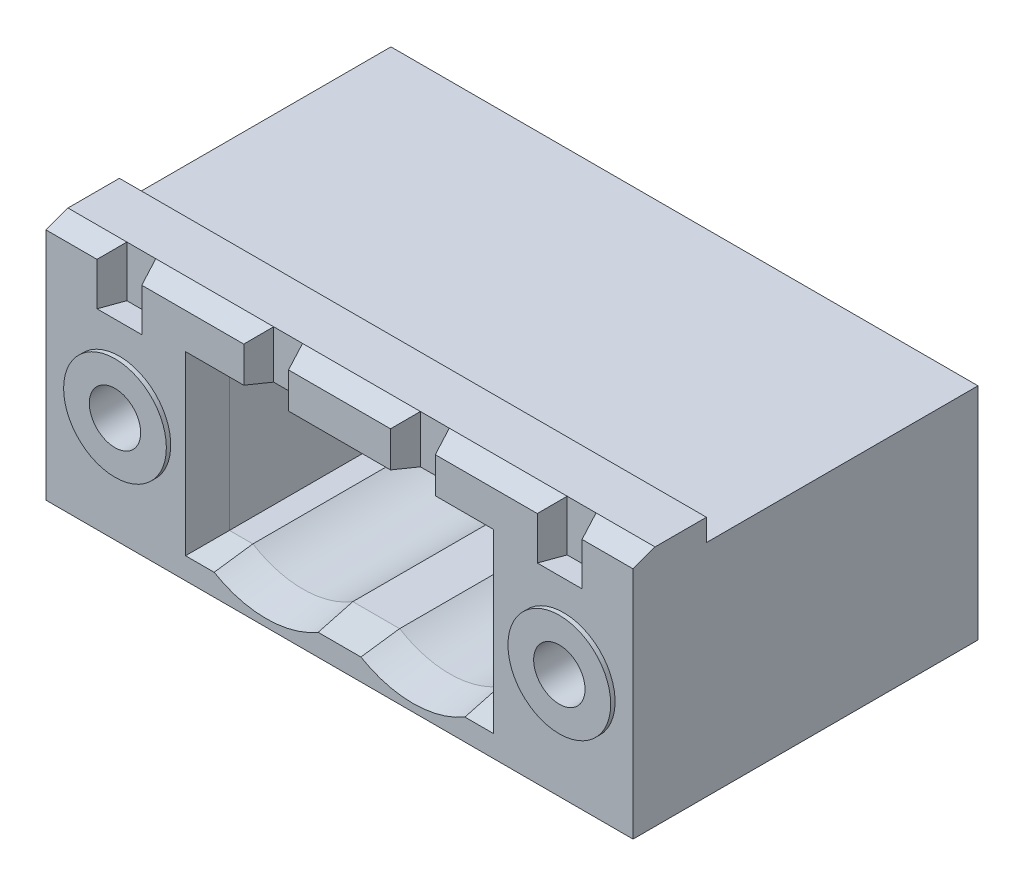
SolidWorks part; units mm, degrees
ref_plane "Front Plane" through (0, 0, 0) normal (0, 0, 1) x (1, 0, 0)
ref_plane "Top Plane" through (0, 0, 0) normal (0, 1, 0) x (1, 0, 0)
ref_plane "Right Plane" through (0, 0, 0) normal (1, 0, 0) x (0, 0, -1)
sketch "Sketch1" plane through (0, 0, 0) normal (1, 0, 0) x (0, 0, -1)
  line L0 (-9.94, -3.81) -> (2, -3.81)
  line L1 (2, -3.81) -> (2, 3.81)
  line L2 (2, 3.81) -> (-7.4, 3.81)
  line L3 (-7.4, 3.81) -> (-7.4, 4.57)
  line L4 (-7.4, 4.57) -> (-9.18, 4.57)
  line L5 (-9.18, 4.57) -> (-9.94, 4.293)
  line L6 (-9.94, 4.293) -> (-9.94, -3.81)
  line L7 (-156.8438, 0) -> (7685.346, 0) construction
  line L8 (0, 0) -> (0, 7842.1898) construction
  point P12 (2, 0)
  dimension "D1" = 11.94
  dimension "D2" = 7.62
  dimension "D3" = 2.54
  dimension "D4" = 0.76
  dimension "D5" = 0.277
  dimension "D6" = 0.76
  dimension "D7" = 2
extrude "Boss-Extrude1" add sketch "Sketch1" along normal mid plane 20.32
sketch "Sketch2" plane through (0, 0, 9.94) normal (0, 0, 1) x (1, 0, 0)
  line L0 (-0.8097, -2.81) -> (0.8097, -2.81)
  line L1 (-5.08, 2.81) -> (5.08, 2.81)
  line L2 (-5.08, 2.81) -> (-5.08, -2.81)
  line L3 (-5.08, -2.81) -> (-4.2703, -2.81)
  line L4 (5.08, 2.81) -> (5.08, -2.81)
  line L5 (4.2703, -2.81) -> (5.08, -2.81)
  arc A0 (-4.2703, -2.81) -> (-0.8097, -2.81) centre (-2.54, 0) ccw
  arc A1 (0.8097, -2.81) -> (4.2703, -2.81) centre (2.54, 0) ccw
  point P4 (0, 2.81)
  point P6 (5.08, 0)
  dimension "D3" = 3.3
  dimension "D1" = 10.16
  dimension "D2" = 5.62
  dimension "D4" = 2.54
  dimension "D5" = 2.54
extrude "Cut-Extrude1" cut sketch "Sketch2" against normal blind 10
chamfer "Chamfer1" distance 0.25 distance2 1.27 8 edges at (-5.08, 0, 9.94) (-4.6751, -2.81, 9.94) (-2.54, -3.3, 9.94) (0, -2.81, 9.94) (2.54, -3.3, 9.94) (4.6751, -2.81, 9.94) (5.08, 0, 9.94) (0, 2.81, 9.94)
sketch "Sketch3" plane through (0, 0, 9.94) normal (0, 0, 1) x (1, 0, 0)
  line L0 (0, 0) -> (-50000, 0) construction
  line L1 (-10.16, 4.293) -> (-10.16, -3.81) construction
  line L2 (0, 0) -> (0, 50000) construction
  line L3 (10.16, 4.293) -> (10.16, -3.81) construction
  circle A0 centre (-7.62, 0) radius 1.778
  circle A1 centre (7.76, 0) radius 1.778
  dimension "D1" = 2.54
  dimension "D2" = 3.556
  dimension "D3" = 2.4
extrude "Boss-Extrude2" add sketch "Sketch3" along normal blind 0.152
sketch "Sketch4" plane through (0, 0, 10.092) normal (0, 0, 1) x (1, 0, 0)
  circle A0 centre (-7.62, 0) radius 0.889
  circle A1 centre (7.76, 0) radius 0.889
  dimension "D1" = 1.778
extrude "Cut-Extrude2" cut sketch "Sketch4" against normal blind 5.08
sketch "Sketch5" plane through (0, 0, -0.06) normal (0, 0, 1) x (1, 0, 0)
  line L0 (0, 0) -> (-50000, 0) construction
  line L1 (0, 0) -> (0, 50000) construction
  line L2 (-2.54, -1000) -> (-2.54, 49000) construction
  line L3 (-3.175, 2.81) -> (-3.175, 1.6629)
  line L4 (5.08, 2.81) -> (-5.08, 2.81) construction
  line L5 (-1.905, 2.81) -> (-1.905, 1.6629)
  line L6 (-3.175, -1.6629) -> (-3.175, -3.2383)
  line L7 (-1.905, -1.6629) -> (-1.905, -3.2383)
  line L8 (-3.175, 2.81) -> (-1.905, 2.81)
  line L9 (-4.2029, 0.635) -> (-5.08, 0.635)
  line L10 (-5.08, 2.81) -> (-5.08, -2.81) construction
  line L11 (-5.08, 0.635) -> (-5.08, -0.635)
  line L12 (-5.08, -0.635) -> (-4.2029, -0.635)
  line L13 (-0.8771, 0.635) -> (0, 0.635)
  line L14 (0, 0.635) -> (0, -0.635)
  line L15 (0, -0.635) -> (-0.8771, -0.635)
  arc A0 (-3.175, 1.6629) -> (-4.2029, 0.635) centre (-2.54, 0) ccw
  arc A1 (-4.2703, -2.81) -> (-0.8097, -2.81) centre (-2.54, 0) ccw construction
  arc A2 (-4.2703, -2.81) -> (-0.8097, -2.81) centre (-2.54, 0) ccw construction
  arc A3 (-1.905, -1.6629) -> (-0.8771, -0.635) centre (-2.54, 0) ccw
  arc A4 (-3.175, -3.2383) -> (-1.905, -3.2383) centre (-2.54, 0) ccw
  arc A5 (-4.2029, -0.635) -> (-3.175, -1.6629) centre (-2.54, 0) ccw
  arc A6 (-0.8771, 0.635) -> (-1.905, 1.6629) centre (-2.54, 0) ccw
  dimension "D2" = 1.78
  dimension "D1" = 2.54
  dimension "D3" = 1.27
  dimension "D4" = 1.27
extrude "Boss-Extrude3" add sketch "Sketch5" along normal blind 0.9525
mirror "Mirror1" about plane through (0, 0, 0) normal (1, 0, 0) of "Boss-Extrude3"
sketch "Sketch8" plane through (0, 0, 0.8925) normal (0, 0, 1) x (1, 0, 0)
  line L0 (0, 0) -> (-50000, 0) construction
  line L1 (-4.2029, 0.635) -> (-3.4904, 0.635)
  line L2 (0.8771, 0.635) -> (1.5896, 0.635)
  line L3 (-1.5896, 0.635) -> (-0.8771, 0.635)
  line L4 (3.4904, 0.635) -> (4.2029, 0.635)
  line L19 (-1.905, 2.81) -> (-3.175, 2.81)
  line L20 (-3.175, 2.81) -> (-3.175, 1.6629)
  line L21 (-4.2029, 0.635) -> (-5.08, 0.635)
  line L22 (-5.08, 0.635) -> (-5.08, -0.635)
  line L23 (-5.08, -0.635) -> (-4.2029, -0.635)
  line L24 (-3.175, -1.6629) -> (-3.175, -3.2383)
  line L25 (-1.905, -3.2383) -> (-1.905, -1.6629)
  line L26 (-0.8771, -0.635) -> (0.8771, -0.635)
  line L27 (1.905, -1.6629) -> (1.905, -3.2383)
  line L28 (3.175, -3.2383) -> (3.175, -1.6629)
  line L29 (4.2029, -0.635) -> (5.08, -0.635)
  line L30 (5.08, -0.635) -> (5.08, 0.635)
  line L31 (5.08, 0.635) -> (4.2029, 0.635)
  line L32 (3.175, 1.6629) -> (3.175, 2.81)
  line L33 (3.175, 2.81) -> (1.905, 2.81)
  line L34 (1.905, 2.81) -> (1.905, 1.6629)
  line L35 (0.8771, 0.635) -> (-0.8771, 0.635)
  line L36 (-1.905, 1.6629) -> (-1.905, 2.81)
  line L39 (-4.2029, 0.635) -> (-5.08, 0.635)
  line L40 (-5.08, 0.635) -> (-5.08, -0.635)
  line L41 (-5.08, -0.635) -> (-4.2029, -0.635)
  line L42 (-3.175, -1.6629) -> (-3.175, -3.2383)
  line L43 (-1.905, -3.2383) -> (-1.905, -1.6629)
  line L44 (-0.8771, -0.635) -> (0.8771, -0.635)
  line L45 (1.905, -1.6629) -> (1.905, -3.2383)
  line L46 (3.175, -3.2383) -> (3.175, -1.6629)
  line L47 (4.2029, -0.635) -> (5.08, -0.635)
  line L48 (5.08, -0.635) -> (5.08, 0.635)
  line L49 (5.08, 0.635) -> (4.2029, 0.635)
  line L53 (0.8771, 0.635) -> (-0.8771, 0.635)
  arc A0 (-3.4904, 0.635) -> (-1.5896, 0.635) centre (-2.54, 0) cw
  arc A1 (1.5896, 0.635) -> (3.4904, 0.635) centre (2.54, 0) cw
  arc A10 (-3.175, 1.6629) -> (-4.2029, 0.635) centre (-2.54, 0) ccw
  arc A11 (-4.2029, -0.635) -> (-3.175, -1.6629) centre (-2.54, 0) ccw
  arc A12 (-3.175, -3.2383) -> (-1.905, -3.2383) centre (-2.54, 0) ccw
  arc A13 (-1.905, -1.6629) -> (-0.8771, -0.635) centre (-2.54, 0) ccw
  arc A14 (0.8771, -0.635) -> (1.905, -1.6629) centre (2.54, 0) ccw
  arc A15 (1.905, -3.2383) -> (3.175, -3.2383) centre (2.54, 0) ccw
  arc A16 (3.175, -1.6629) -> (4.2029, -0.635) centre (2.54, 0) ccw
  arc A17 (4.2029, 0.635) -> (3.175, 1.6629) centre (2.54, 0) ccw
  arc A18 (1.905, 1.6629) -> (0.8771, 0.635) centre (2.54, 0) ccw
  arc A19 (-0.8771, 0.635) -> (-1.905, 1.6629) centre (-2.54, 0) ccw
  arc A21 (-4.2029, -0.635) -> (-3.175, -1.6629) centre (-2.54, 0) ccw
  arc A22 (-3.175, -3.2383) -> (-1.905, -3.2383) centre (-2.54, 0) ccw
  arc A23 (-1.905, -1.6629) -> (-0.8771, -0.635) centre (-2.54, 0) ccw
  arc A24 (0.8771, -0.635) -> (1.905, -1.6629) centre (2.54, 0) ccw
  arc A25 (1.905, -3.2383) -> (3.175, -3.2383) centre (2.54, 0) ccw
  arc A26 (3.175, -1.6629) -> (4.2029, -0.635) centre (2.54, 0) ccw
  dimension "D2" = 1.143
  dimension "D1" = 0
extrude "Boss-Extrude4" add sketch "Sketch8" along normal blind 0.318
sketch "Sketch9" plane through (0, 0, 1.2105) normal (0, 0, 1) x (1, 0, 0)
  circle A0 centre (-2.54, 0) radius 1.143
  circle A1 centre (2.54, 0) radius 1.143
extrude "Boss-Extrude5" add sketch "Sketch9" along normal blind 0.635
sketch "Sketch10" plane through (0, 4.57, 0) normal (0, 1, 0) x (1, 0, 0)
  line L0 (-2.04, -9.18) -> (-1.765, -9.94)
  line L2 (-3.04, -9.18) -> (-2.04, -9.18)
  line L4 (-3.315, -9.94) -> (-3.04, -9.18)
  line L6 (-7.62, -1005.012) -> (-7.62, 48994.988) construction
  line L7 (-8.509, -5.012) -> (-6.731, -5.012) construction
  line L8 (-8.395, -9.94) -> (-8.12, -9.18)
  line L9 (10.16, -9.94) -> (-10.16, -9.94) construction
  line L10 (10.16, -9.18) -> (-10.16, -9.18) construction
  line L11 (-8.12, -9.18) -> (-7.12, -9.18)
  line L12 (-7.12, -9.18) -> (-6.845, -9.94)
  line L13 (-6.845, -9.94) -> (-8.395, -9.94)
  line L26 (-1.765, -9.94) -> (-3.315, -9.94)
  line L27 (3.04, -9.18) -> (3.315, -9.94)
  line L28 (2.04, -9.18) -> (3.04, -9.18)
  line L29 (1.765, -9.94) -> (2.04, -9.18)
  line L30 (3.315, -9.94) -> (1.765, -9.94)
  line L31 (8.12, -9.18) -> (8.395, -9.94)
  line L32 (7.12, -9.18) -> (8.12, -9.18)
  line L33 (6.845, -9.94) -> (7.12, -9.18)
  line L34 (8.395, -9.94) -> (6.845, -9.94)
  line L35 (-7.12, -9.18) -> (-2.04, -9.18) construction
  point P20 (-7.62, -5.012)
  dimension "D1" = 1
  dimension "D2" = 1.55
  dimension "D4" = 5.08
  dimension "D3" = 4
extrude "Cut-Extrude3" cut sketch "Sketch10" against normal up to surface (1.76 mm away) up to face at (0, 2.81, 1.7125)
sketch "Sketch11" plane through (0, -3.81, 0) normal (0, -1, 0) x (1, 0, 0)
  line L0 (-10.16, 9.94) -> (-10.16, -2) construction
  line L1 (10.16, 9.94) -> (10.16, -2) construction
  line L2 (10.16, -2) -> (-10.16, -2) construction
  circle A0 centre (-7.62, 2) radius 0.64
  circle A1 centre (7.62, 2) radius 0.64
  dimension "D1" = 2.54
  dimension "D3" = 4
  dimension "D4" = 1.28
  dimension "D2" = 2.54
extrude "Cut-Extrude4" cut sketch "Sketch11" against normal blind 6.7
sketch "Sketch12" plane through (0, 0, -2) normal (0, 0, -1) x (-1, 0, 0)
  circle A0 centre (-7.76, 0) radius 0.64
  circle A1 centre (7.62, 0) radius 0.64
  dimension "D1" = 1.28
extrude "Cut-Extrude6" cut sketch "Sketch12" against normal blind 4
ref_plane "Plane2" through (2.54, 0, 0) normal (1, 0, 0) x (0, 0, -1)
sketch "Sketch13" plane through (2.54, 0, 0) normal (1, 0, 0) x (0, 0, -1)
  line L0 (2, -3.81) -> (2, 2.79)
  line L1 (2, -3.81) -> (2, 3.81) construction
  line L2 (2, 2.79) -> (1.49, 2.79)
  line L3 (1.49, 2.79) -> (1.49, 1.02)
  line L4 (1.49, 1.02) -> (0.73, 1.02)
  line L5 (0.73, 1.02) -> (0.73, -3.56)
  line L6 (0.73, -3.56) -> (-0.92, -3.56)
  line L7 (-0.92, -3.56) -> (-1.17, -3.81)
  line L8 (-9.94, -3.81) -> (2, -3.81) construction
  line L9 (-1.17, -3.81) -> (2, -3.81)
  dimension "D1" = 6.6
  dimension "D2" = 4.83
  dimension "D3" = 0.51
  dimension "D4" = 0.76
  dimension "D5" = 2.92
  dimension "D6" = 45
  dimension "D7" = 0.25
extrude "Cut-Extrude7" cut sketch "Sketch13" against normal mid plane 2.54
mirror "Mirror2" about plane through (0, 0, 0) normal (1, 0, 0) of "Cut-Extrude7"
sketch "Sketch15" plane through (0, 0, 1.8455) normal (0, 0, 1) x (1, 0, 0)
  circle A0 centre (-2.54, 0) radius 0.125
  circle A1 centre (2.54, 0) radius 0.125
  dimension "D1" = 0.25
extrude "Cut-Extrude8" cut sketch "Sketch15" against normal through all
